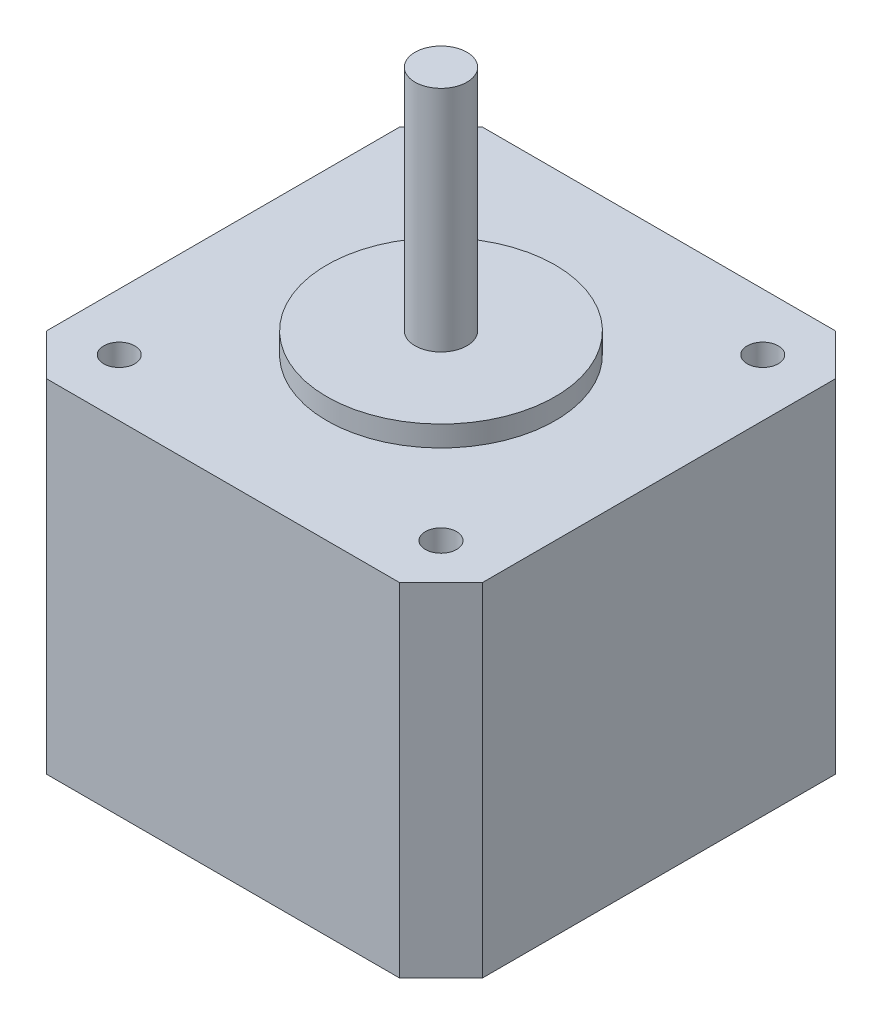
SolidWorks part; units mm, degrees
ref_plane "Front Plane" through (0, 0, 0) normal (0, 0, 1) x (1, 0, 0)
ref_plane "Top Plane" through (0, 0, 0) normal (0, 1, 0) x (1, 0, 0)
ref_plane "Right Plane" through (0, 0, 0) normal (1, 0, 0) x (0, 0, -1)
sketch "Sketch1" plane through (0, 0, 0) normal (0, 1, 0) x (1, 0, 0)
  line L0 (0, 21) -> (0, -21) construction
  line L1 (-21, 21) -> (21, 21)
  line L2 (-21, 21) -> (-21, -21)
  line L3 (-21, -21) -> (21, -21)
  line L4 (21, 21) -> (21, -21)
  line L7 (-21, 0) -> (21, 0) construction
  circle A0 centre (15.5, 15.5) radius 1.5
  circle A1 centre (-15.5, 15.5) radius 1.5
  circle A2 centre (15.5, -15.5) radius 1.5
  circle A3 centre (-15.5, -15.5) radius 1.5
  circle A4 centre (0, 0) radius 21.9203 construction
  point P0 (0, 0)
  point P9 (0, 0)
  point P12 (0, 0)
  dimension "D3" = 31
  dimension "D5" = 43.8406
  dimension "D1" = 42
  dimension "D2" = 42
  dimension "D4" = 31
extrude "Boss-Extrude1" add sketch "Sketch1" along normal blind 33
chamfer "Chamfer1" distance 4 angle 45 4 edges at (-21, 16.5, 21) (-21, 16.5, -21) (21, 16.5, -21) (21, 16.5, 21)
sketch "Sketch2" plane through (0, 33, 0) normal (0, 1, 0) x (1, 0, 0)
  circle A0 centre (0, 0) radius 11
extrude "Boss-Extrude2" add sketch "Sketch2" along normal blind 2
sketch "Sketch3" plane through (0, 35, 0) normal (0, 1, 0) x (1, 0, 0)
  circle A0 centre (0, 0) radius 2.5
extrude "Boss-Extrude3" add sketch "Sketch3" along normal blind 22
